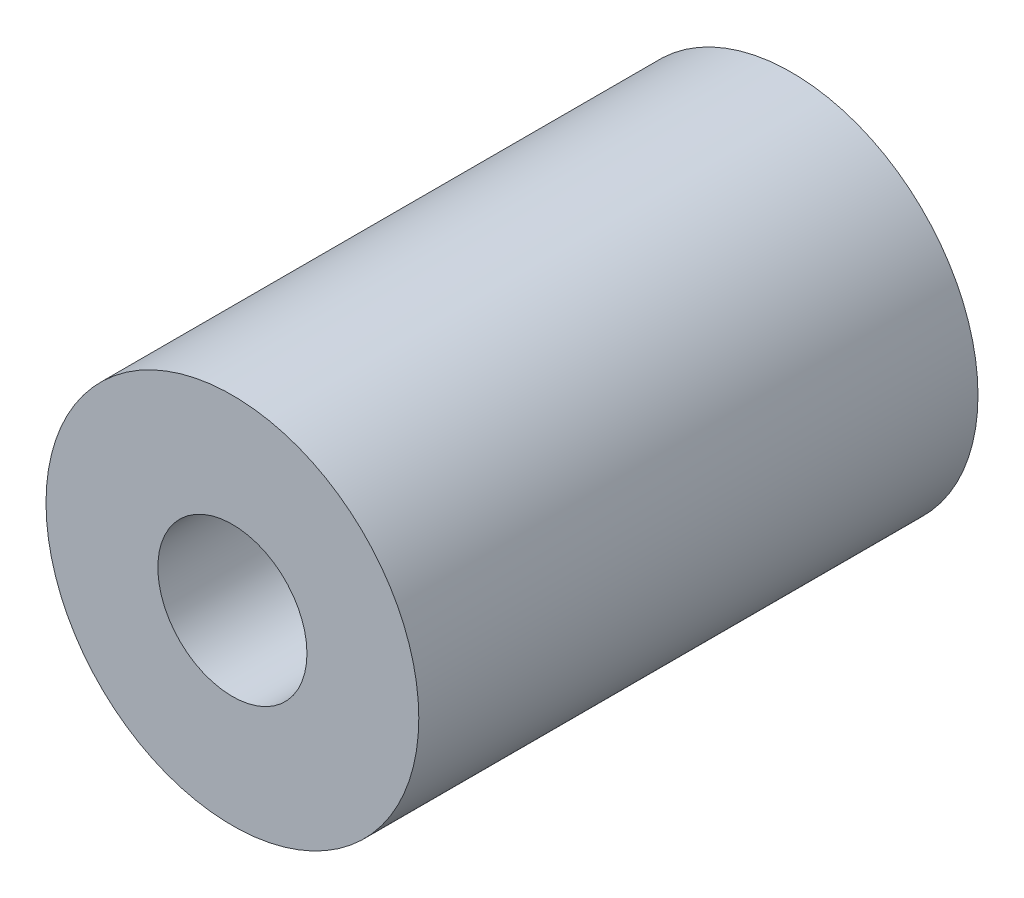
SolidWorks part; units mm, degrees
ref_plane "前视基准面" through (0, 0, 0) normal (0, 0, 1) x (1, 0, 0)
ref_plane "上视基准面" through (0, 0, 0) normal (0, 1, 0) x (1, 0, 0)
ref_plane "右视基准面" through (0, 0, 0) normal (1, 0, 0) x (0, 0, -1)
other "Configuration Table"
sketch "草图1" plane through (0, 0, 0) normal (0, 0, 1) x (1, 0, 0)
  circle A0 centre (0, 0) radius 2
  circle A1 centre (0, 0) radius 5
  dimension "D1" = 4
  dimension "D2" = 10
extrude "凸台-拉伸1" add sketch "草图1" along normal blind 15
